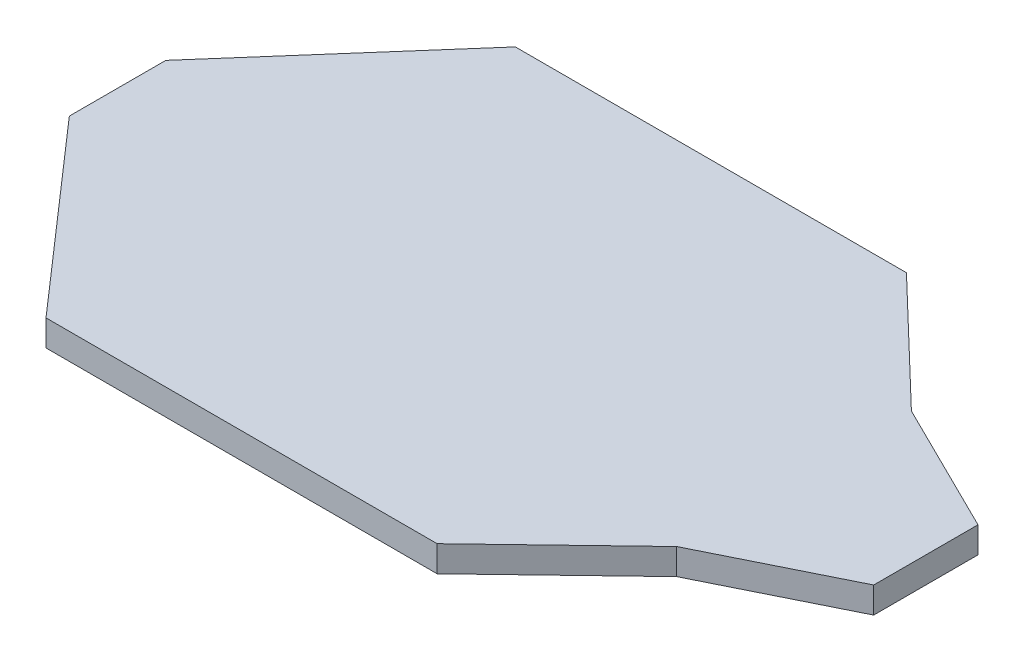
SolidWorks part; units mm, degrees
ref_plane "Front Plane" through (0, 0, 0) normal (0, 0, 1) x (1, 0, 0)
ref_plane "Top Plane" through (0, 0, 0) normal (0, 1, 0) x (1, 0, 0)
ref_plane "Right Plane" through (0, 0, 0) normal (1, 0, 0) x (0, 0, -1)
sketch "Initial Measurements" plane through (0, 0, 0) normal (0, 1, 0) x (1, 0, 0)
  line L0 (0, 18.5) -> (62.552, 90)
  line L1 (0, 0) -> (310, 0) construction
  line L2 (0, 0) -> (0, 18.5)
  line L4 (310, 0) -> (310, 20)
  line L5 (62.552, 90) -> (212.552, 90)
  line L6 (212.552, 90) -> (259.4561, 45)
  line L7 (259.4561, 45) -> (310, 20)
  line L8 (310, 20) -> (241, 20) construction
  line L9 (234.5, 26.5) -> (287.5, 26.5) construction
  line L10 (310, 17.05) -> (303, 17.05) construction
  line L11 (234.5, 26.5) -> (241, 20) construction
  line L12 (287.5, 26.5) -> (281, 20) construction
  line L13 (0, 7.5) -> (5, 7.5) construction
  line L14 (-26.8471, 33.5) -> (115.845, 33.5) construction
  circle A1 centre (281, 20) radius 1.7
  circle A2 centre (287.5, 26.5) radius 1.7
  circle A3 centre (234.5, 26.5) radius 1.7
  circle A4 centre (241, 20) radius 1.7
  circle A5 centre (303, 17.05) radius 2.25
  circle A6 centre (5, 7.5) radius 1.65
  circle A7 centre (36.2555, 33.5) radius 7.6073
  circle A8 centre (77.4697, 33.5) radius 7.6073
  dimension "D9" = 3.4
  dimension "D10" = 4.5
  dimension "D17" = 3.3
  dimension "D1" = 18.5
  dimension "D2" = 90
  dimension "D3" = 45
  dimension "D4" = 20
  dimension "D5" = 310
  dimension "D6" = 150
  dimension "D7" = 65
  dimension "D8" = 95
  dimension "D11" = 17.05
  dimension "D12" = 26.5
  dimension "D13" = 40
  dimension "D14" = 53
  dimension "D15" = 7
  dimension "D16" = 29
  dimension "D18" = 7.5
  dimension "D19" = 5
  dimension "D20" = 33.5
sketch "Sketch2" plane through (0, 0, 0) normal (0, 1, 0) x (1, 0, 0)
  line L0 (0, 0) -> (310, 0) construction
  line L1 (310, 0) -> (310, 20) construction
  line L2 (259.4561, 45) -> (310, 20) construction
  line L3 (212.552, 90) -> (259.4561, 45) construction
  line L4 (0, 0) -> (0, 18.5) construction
  line L5 (0, 18.5) -> (62.552, 90) construction
  line L6 (62.552, 90) -> (212.552, 90) construction
  line L7 (0, 0) -> (310, 0) construction
  line L8 (310, -20) -> (310, 20)
  line L9 (259.4561, 45) -> (310, 20)
  line L10 (212.552, 90) -> (259.4561, 45)
  line L11 (0, -18.5) -> (0, 18.5)
  line L12 (0, 18.5) -> (62.552, 90)
  line L13 (62.552, 90) -> (212.552, 90)
  line L14 (62.552, -90) -> (212.552, -90)
  line L15 (0, -18.5) -> (62.552, -90)
  line L16 (212.552, -90) -> (259.4561, -45)
  line L17 (259.4561, -45) -> (310, -20)
extrude "Boss-Extrude1" add sketch "Sketch2" along normal blind 10
